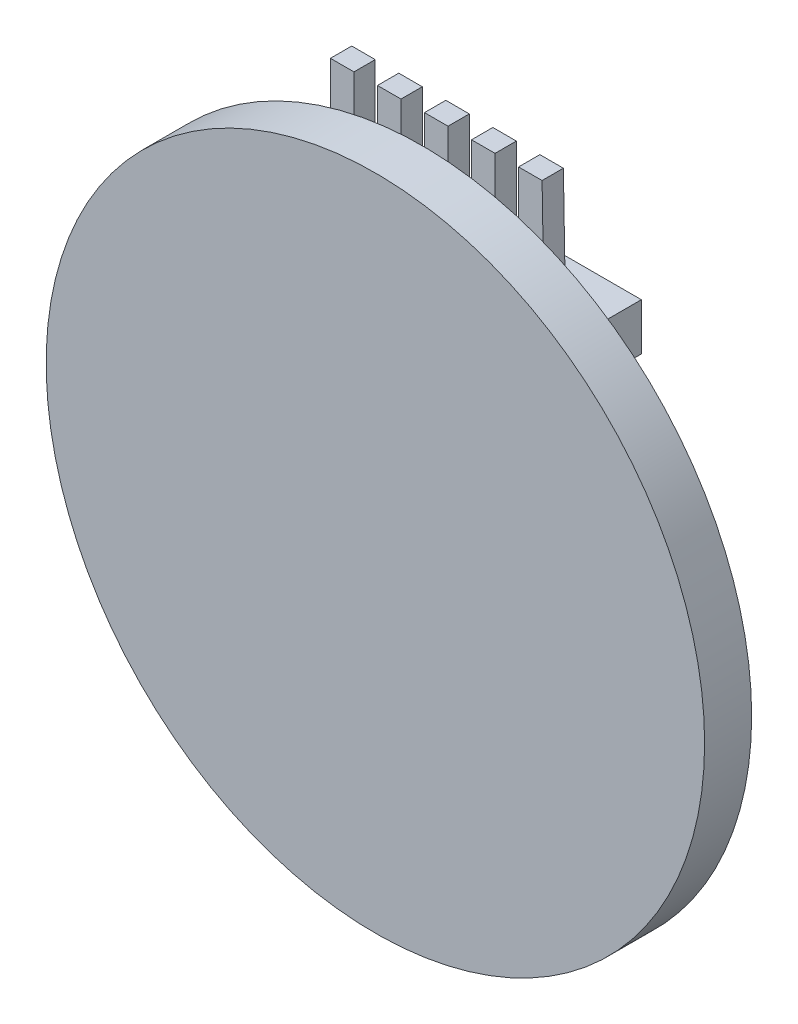
SolidWorks part; units mm, degrees
ref_plane "Front Plane" through (0, 0, 0) normal (0, 0, 1) x (1, 0, 0)
ref_plane "Top Plane" through (0, 0, 0) normal (0, 1, 0) x (1, 0, 0)
ref_plane "Right Plane" through (0, 0, 0) normal (1, 0, 0) x (0, 0, -1)
sketch "Sketch1" plane through (0, 0, 0) normal (0, 0, 1) x (1, 0, 0)
  circle A0 centre (0, 0) radius 7
  dimension "D1" = 14
extrude "Boss-Extrude1" add sketch "Sketch1" along normal blind 1
sketch "Sketch2" plane through (0, 0, 0) normal (0, 0, -1) x (-1, 0, 0)
  line L1 (-2.6546, 4.4929) -> (2.3454, 4.4929)
  line L2 (-2.6546, 4.4929) -> (-2.6546, 3.4929)
  line L3 (-2.6546, 3.4929) -> (2.3454, 3.4929)
  line L4 (2.3454, 4.4929) -> (2.3454, 3.4929)
  line L5 (-2.6546, 4.4929) -> (2.3454, 3.4929) construction
  line L6 (-2.6546, 3.4929) -> (2.3454, 4.4929) construction
  point P4 (-0.1546, 3.9929)
  dimension "D1" = 1
  dimension "D2" = 5
extrude "Boss-Extrude2" add sketch "Sketch2" along normal blind 2
sketch "Sketch3" plane through (0, 4.4929, 0) normal (0, 1, 0) x (1, 0, 0)
  line L0 (1.4046, 0.1395) -> (0.9046, 0.1395)
  line L1 (2.4046, 0.1395) -> (1.9046, 0.1395)
  line L2 (2.4046, 0.1395) -> (2.4046, 0.5923)
  line L3 (2.4046, 0.5923) -> (1.9046, 0.5923)
  line L4 (1.9046, 0.1395) -> (1.9046, 0.5923)
  line L5 (2.4046, 0.1395) -> (1.9046, 0.5923) construction
  line L6 (2.4046, 0.5923) -> (1.9046, 0.1395) construction
  line L7 (1.4046, 0.1395) -> (1.4046, 0.5923)
  line L8 (1.4046, 0.5923) -> (0.9046, 0.5923)
  line L9 (0.9046, 0.1395) -> (0.9046, 0.5923)
  line L10 (1.4046, 0.1395) -> (0.9046, 0.5923) construction
  line L11 (1.4046, 0.5923) -> (0.9046, 0.1395) construction
  line L12 (0.4046, 0.1395) -> (-0.0954, 0.1395)
  line L13 (0.4046, 0.1395) -> (0.4046, 0.5923)
  line L14 (0.4046, 0.5923) -> (-0.0954, 0.5923)
  line L15 (-0.0954, 0.1395) -> (-0.0954, 0.5923)
  line L16 (0.4046, 0.1395) -> (-0.0954, 0.5923) construction
  line L17 (0.4046, 0.5923) -> (-0.0954, 0.1395) construction
  line L18 (-0.5954, 0.1395) -> (-1.0954, 0.1395)
  line L19 (-0.5954, 0.1395) -> (-0.5954, 0.5923)
  line L20 (-0.5954, 0.5923) -> (-1.0954, 0.5923)
  line L21 (-1.0954, 0.1395) -> (-1.0954, 0.5923)
  line L22 (-0.5954, 0.1395) -> (-1.0954, 0.5923) construction
  line L23 (-0.5954, 0.5923) -> (-1.0954, 0.1395) construction
  line L24 (-1.5954, 0.1395) -> (-2.0954, 0.1395)
  line L25 (-1.5954, 0.1395) -> (-1.5954, 0.5923)
  line L26 (-1.5954, 0.5923) -> (-2.0954, 0.5923)
  line L27 (-2.0954, 0.1395) -> (-2.0954, 0.5923)
  line L28 (-1.5954, 0.1395) -> (-2.0954, 0.5923) construction
  line L29 (-1.5954, 0.5923) -> (-2.0954, 0.1395) construction
  line L30 (-2.3454, 2) -> (-2.3454, 0) construction
  line L31 (2.6546, 2) -> (2.6546, 0) construction
  point P4 (2.1546, 0.3659)
  point P10 (1.1546, 0.3659)
  point P15 (0.1546, 0.3659)
  point P20 (-0.8454, 0.3659)
  point P25 (-1.8454, 0.3659)
  dimension "D1" = 0.25
  dimension "D2" = 0.25
  dimension "D3" = 0.5
  dimension "D4" = 0.5
  dimension "D5" = 0.5
  dimension "D6" = 0.5
  dimension "D7" = 0.5
  dimension "D8" = 0.5
  dimension "D9" = 0.5
  dimension "D10" = 0.5
  dimension "D11" = 0.5
extrude "Boss-Extrude3" add sketch "Sketch3" along normal blind 3
draft "Draft9" type of draft neutral plane draft angle 1 faces to draft 1 face at (2.4046, 5.9929, -0.3659) neutral plane through (0, 7.4929, 0) neutral plane normal (0, 1, 0) parameters "D1"=1
